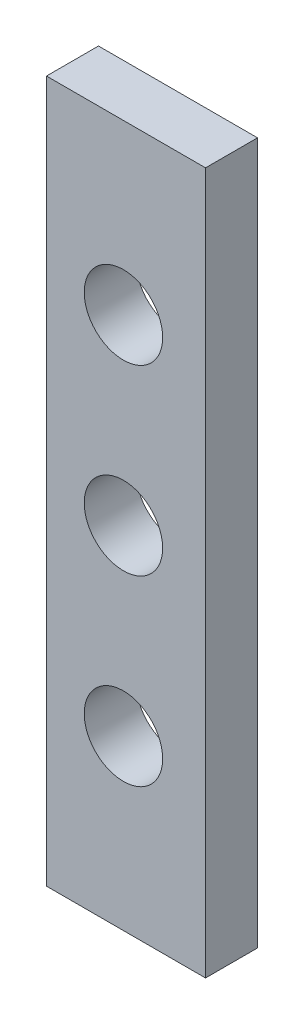
SolidWorks part; units mm, degrees
ref_plane "前视基准面" through (0, 0, 0) normal (0, 0, 1) x (1, 0, 0)
ref_plane "上视基准面" through (0, 0, 0) normal (0, 1, 0) x (1, 0, 0)
ref_plane "右视基准面" through (0, 0, 0) normal (1, 0, 0) x (0, 0, -1)
sketch "草图1" plane through (0, 0, 0) normal (0, 0, 1) x (1, 0, 0)
  line L0 (-121.2816, -66.5374) -> (-121.2816, -105) construction
  line L1 (-130, -105) -> (-121.2816, -105)
  line L2 (-130, -105) -> (-130, -66.5374)
  line L3 (-130, -66.5374) -> (-121.2816, -66.5374)
  line L4 (-121.2816, -105) -> (-121.2816, -66.5374)
  line L5 (-121.2816, -66.5374) -> (-121.2816, -105) construction
  dimension "D1" = 8.7184
  dimension "D2" = 38.4626
extrude "凸台-拉伸1" add sketch "草图1" along normal offset from surface (2.85 mm away) 0.15
hole_wizard "打孔尺寸(%根据十字)槽沉头木螺钉的类型1" positions "草图2" profile "草图3" countersink size "M4" standard "GB"
sketch "草图2" plane through (40.4914, -131.0101, 7) normal (0, 0, 1) x (0, 1, 0)
  point P0 (35.2414, 166.273)
  point P3 (45.2414, 166.273)
  point P6 (55.2414, 166.273)
  point P9 (206.7788, 166.273)
  point P12 (216.7788, 166.273)
  point P15 (226.7788, 166.273)
sketch "草图3" plane through (-125.7816, -95.7687, 7) normal (1, 0, 0) x (0, -1, 0)
  line L0 (0, 0) -> (0, 20.2919)
  line L1 (0, 20.2919) -> (2.15, 19)
  line L2 (2.15, 19) -> (2.15, 1.85)
  line L3 (2.15, 1.85) -> (4, 0)
  line L4 (4, 0) -> (0, 0)
  line L5 (-2.15, 1.85) -> (-4, 0) construction
  line L6 (0, 20.2919) -> (-2.15, 19) construction
  line L7 (0, -6.35) -> (0, 107.95) construction
  dimension "孔直径" = 4.3
  dimension "孔深度" = 19
  dimension "近端锥形沉头孔直径" = 8
  dimension "近端锥形沉头孔角度" = 90
  dimension "导头角度" = 118
